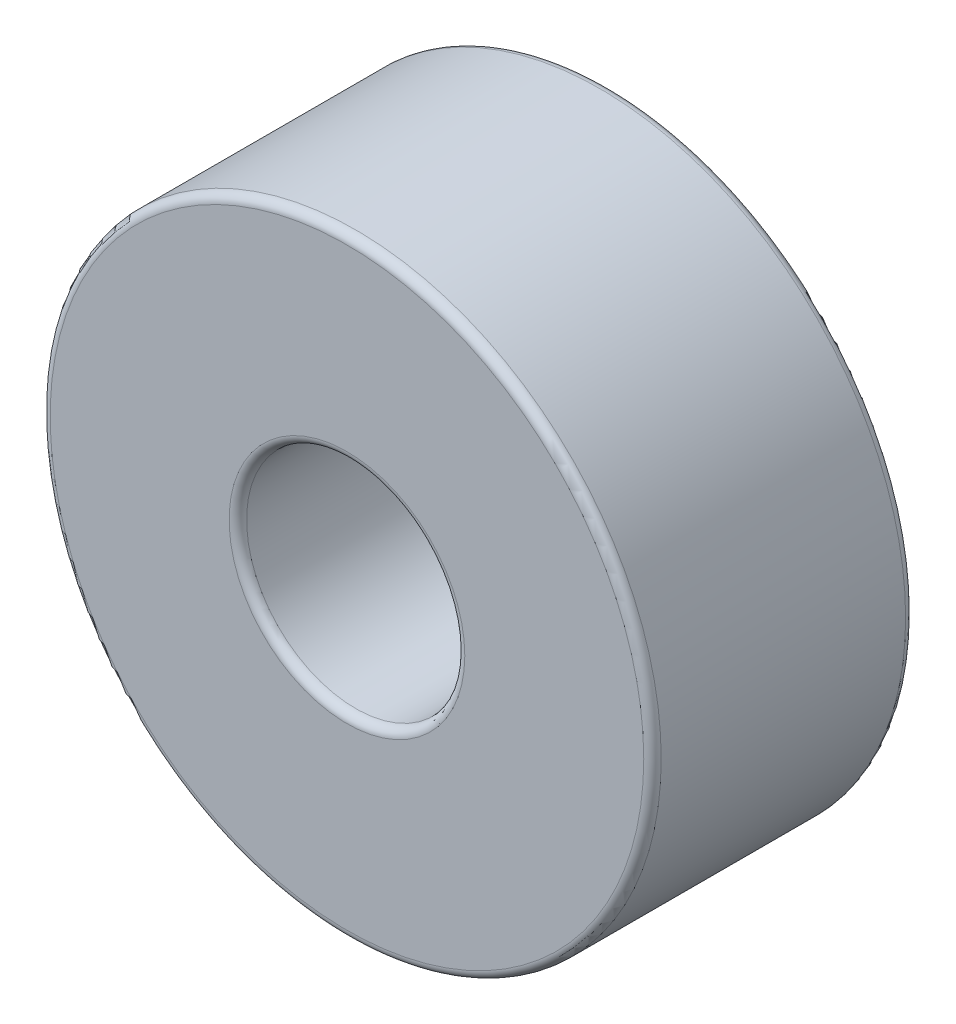
SolidWorks part; units mm, degrees
ref_plane "前视基准面" through (0, 0, 0) normal (0, 0, 1) x (1, 0, 0)
ref_plane "上视基准面" through (0, 0, 0) normal (0, 1, 0) x (1, 0, 0)
ref_plane "右视基准面" through (0, 0, 0) normal (1, 0, 0) x (0, 0, -1)
sketch "草图1" plane through (0, 0, 0) normal (0, 0, 1) x (1, 0, 0)
  circle A0 centre (0, 0) radius 7
  dimension "D1" = 14
extrude "凸台-拉伸1" add sketch "草图1" along normal blind 6
sketch "草图2" plane through (0, 0, 6) normal (0, 0, 1) x (1, 0, 0)
  circle A0 centre (0, 0) radius 2.5
  dimension "D1" = 5
extrude "切除-拉伸1" cut sketch "草图2" against normal through all
fillet "圆角1" radius 0.2 4 edges at (2.5, 0, 0) (7, 0, 0) (7, 0, 6) (2.5, 0, 6)
